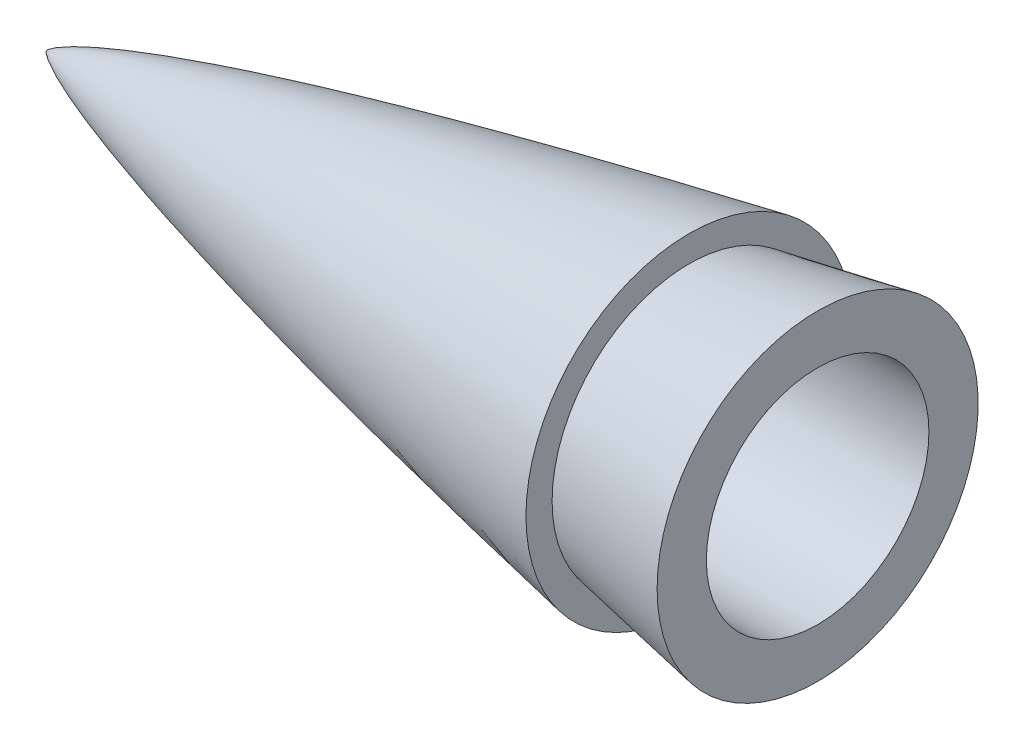
SolidWorks part; units mm, degrees
material "6061-T6 (SS)"
ref_plane "Front Plane" through (0, 0, 0) normal (0, 0, 1) x (1, 0, 0)
ref_plane "Top Plane" through (0, 0, 0) normal (0, 1, 0) x (1, 0, 0)
ref_plane "Right Plane" through (0, 0, 0) normal (1, 0, 0) x (0, 0, -1)
sketch "Sketch3" plane through (0, 0, 0) normal (0, 0, 1) x (1, 0, 0)
  line L0 (0, 0) -> (750, 0) construction
  line L1 (750, 75) -> (750, 0) construction
  line L4 (50, 0) -> (50, 12.6904) construction
  line L5 (60, 8.6554) -> (50, 8.6554)
  line L8 (60, 8.6554) -> (60, 12.4875)
  line L9 (60, 8.6554) -> (39.6894, 8.6554)
  line L10 (60, 12.4875) -> (50, 10.6554)
  line L11 (50, 10.6554) -> (50, 12.6904)
  line L12 (0, 0) -> (4.5526, 0)
  line L13 (4.5526, 0) -> (39.6894, 8.6554)
  spline S0 degree 4 poles (0, 0) (0.0027, 0.0074) (0.0091, 0.0215) (0.0269, 0.047) (0.0684, 0.0933) (0.1314, 0.151) (0.2168, 0.2183) (0.3382, 0.3041) (0.4839, 0.3974) (0.6551, 0.4981) (0.8516, 0.6056) (1.1377, 0.7534) (1.5815, 0.9661) (2.3351, 1.2961) (3.6829, 1.8266) (6.1115, 2.6745) (10.5746, 4.038) (18.9517, 6.252) (33.5701, 9.5653) (58.4067, 14.4079) (92.5079, 20.1209) (133.842, 26.2251) (179.8092, 32.3065) (225.8421, 37.8632) (271.9254, 42.9839) (318.0491, 47.7253) (364.2071, 52.1207) (410.3947, 56.191) (456.6091, 59.9459) (502.848, 63.3865) (549.1098, 66.5042) (595.3934, 69.2798) (635.9102, 71.3773) (670.652, 72.8985) (698.6683, 73.9066) (717.5285, 74.458) (733.0226, 74.8041) (742.7236, 74.948) (747.5745, 74.994) (750, 75) knots 0 0 0 0 0 0.000041 0.000082 0.000164 0.000329 0.000493 0.000658 0.000951 0.001245 0.001545 0.001844 0.002657 0.003853 0.005902 0.009516 0.016281 0.028569 0.051794 0.088907 0.150314 0.211721 0.273128 0.334535 0.395942 0.457348 0.518755 0.580162 0.641569 0.702976 0.764383 0.825789 0.887196 0.9179 0.948603 0.974302 0.987151 1 1 1 1 1 construction
  spline S1 degree 4 poles (0, 0) (0.0027, 0.0074) (0.0091, 0.0215) (0.0269, 0.047) (0.0684, 0.0933) (0.1314, 0.151) (0.2168, 0.2183) (0.3382, 0.3041) (0.4839, 0.3974) (0.6551, 0.4981) (0.8516, 0.6056) (1.1377, 0.7534) (1.5815, 0.9661) (2.3351, 1.2961) (3.6829, 1.8266) (6.1115, 2.6745) (10.5746, 4.038) (18.9517, 6.252) (33.5701, 9.5653) (58.4067, 14.4079) (92.5079, 20.1209) (133.842, 26.2251) (179.8092, 32.3065) (225.8421, 37.8632) (271.9254, 42.9839) (318.0491, 47.7253) (364.2071, 52.1207) (410.3947, 56.191) (456.6091, 59.9459) (502.848, 63.3865) (549.1098, 66.5042) (595.3934, 69.2798) (635.9102, 71.3773) (670.652, 72.8985) (698.6683, 73.9066) (717.5285, 74.458) (733.0226, 74.8041) (742.7236, 74.948) (747.5745, 74.994) (750, 75) knots 0 0 0 0 0 0.000041 0.000082 0.000164 0.000329 0.000493 0.000658 0.000951 0.001245 0.001545 0.001844 0.002657 0.003853 0.005902 0.009516 0.016281 0.028569 0.051794 0.088907 0.150314 0.211721 0.273128 0.334535 0.395942 0.457348 0.518755 0.580162 0.641569 0.702976 0.764383 0.825789 0.887196 0.9179 0.948603 0.974302 0.987151 1 1 1 1 1 construction
  spline S2 degree 1 poles (1.4903, -1.3338) (750.005, 73) knots 0 0 1 1 construction
  spline S3 degree 3 poles (1.4903, -1.3338) (1.5589, -1.2901) (1.6884, -1.215) (2.0463, -1.0265) (2.5333, -0.7992) (3.1596, -0.5329) (3.7794, -0.2875) (4.3018, -0.0911) (4.7453, 0.0703) (5.4421, 0.3177) (6.9404, 0.8231) (9.2452, 1.5349) (12.978, 2.5975) (17.6948, 3.8203) (23.3974, 5.1816) (29.1253, 6.4628) (34.0795, 7.5135) (38.0831, 8.334) (41.4609, 9.0109) (44.5462, 9.6155) (48.3348, 10.3435) (51.6647, 10.9694) (54.9972, 11.5836) (58.3315, 12.1902) (63.1875, 13.0579) (71.0794, 14.4302) (81.1803, 16.1199) (96.685, 18.6056) (116.096, 21.5466) (139.4233, 24.8657) (162.7777, 28.0087) (193.9457, 31.9976) (232.9503, 36.6516) (279.809, 41.7958) (326.7103, 46.554) (373.6471, 50.959) (420.6145, 55.0304) (483.2742, 60.024) (545.9829, 64.3695) (608.7338, 67.9946) (655.8157, 70.3049) (695.0668, 71.8209) (722.5426, 72.5832) (738.2468, 72.8875) (746.0841, 72.9903) (750.005, 73) knots 0.00073 0.00073 0.00073 0.00073 0.001218 0.001706 0.002682 0.003658 0.004634 0.005493 0.00598 0.006585 0.008537 0.01244 0.016344 0.02415 0.031957 0.039764 0.047571 0.052144 0.056048 0.061293 0.064665 0.07141 0.074782 0.078154 0.084898 0.094412 0.110025 0.125639 0.156866 0.188093 0.21932 0.250548 0.313002 0.375456 0.437911 0.500365 0.562819 0.625274 0.750183 0.812637 0.875091 0.937546 0.968773 0.984386 1 1 1 1 construction
  spline S4 degree 4 poles (0, 0) (0.0027, 0.0074) (0.0091, 0.0215) (0.0269, 0.047) (0.0684, 0.0933) (0.1314, 0.151) (0.2168, 0.2183) (0.3382, 0.3041) (0.4839, 0.3974) (0.6551, 0.4981) (0.8516, 0.6056) (1.1377, 0.7534) (1.5815, 0.9661) (2.3351, 1.2961) (3.6829, 1.8266) (6.1115, 2.6745) (10.5746, 4.038) (18.9517, 6.252) (33.5701, 9.5653) (58.4067, 14.4079) (92.5079, 20.1209) (133.842, 26.2251) (179.8092, 32.3065) (225.8421, 37.8632) (271.9254, 42.9839) (318.0491, 47.7253) (364.2071, 52.1207) (410.3947, 56.191) (456.6091, 59.9459) (502.848, 63.3865) (549.1098, 66.5042) (595.3934, 69.2798) (635.9102, 71.3773) (670.652, 72.8985) (698.6683, 73.9066) (717.5285, 74.458) (733.0226, 74.8041) (742.7236, 74.948) (747.5745, 74.994) (750, 75) knots 0 0 0 0 0 0.000041 0.000082 0.000164 0.000329 0.000493 0.000658 0.000951 0.001245 0.001545 0.001844 0.002657 0.003853 0.005902 0.009516 0.016281 0.028569 0.051794 0.088907 0.150314 0.211721 0.273128 0.334535 0.395942 0.457348 0.518755 0.580162 0.641569 0.702976 0.764383 0.825789 0.887196 0.9179 0.948603 0.974302 0.987151 1 1 1 1 1 construction
  spline S5 degree 4 poles (0, 0) (0.0027, 0.0074) (0.0091, 0.0215) (0.0269, 0.047) (0.0684, 0.0933) (0.1314, 0.151) (0.2168, 0.2183) (0.3382, 0.3041) (0.4839, 0.3974) (0.6551, 0.4981) (0.8516, 0.6056) (1.1377, 0.7534) (1.5815, 0.9661) (2.3351, 1.2961) (3.6829, 1.8266) (6.1115, 2.6745) (10.5746, 4.038) (18.9517, 6.252) (29.819, 8.7151) (39.4848, 10.6852) (46.8939, 12.1075) (50, 12.6904) knots 0 0 0 0 0 0.000041 0.000082 0.000164 0.000329 0.000493 0.000658 0.000951 0.001245 0.001545 0.001844 0.002657 0.003853 0.005902 0.009516 0.016281 0.028569 0.051794 0.068536 0.068536 0.068536 0.068536 0.068536
  point P9 (0, 0)
  point P14 (758.3567, 75)
  dimension "D1" = 75
  dimension "D2" = 750
  dimension "D4" = 50
  dimension "D5" = 2
  dimension "D6" = 10
  dimension "D3" = 2
revolve "Revolve2" add sketch "Sketch3" angle 360 about L0
